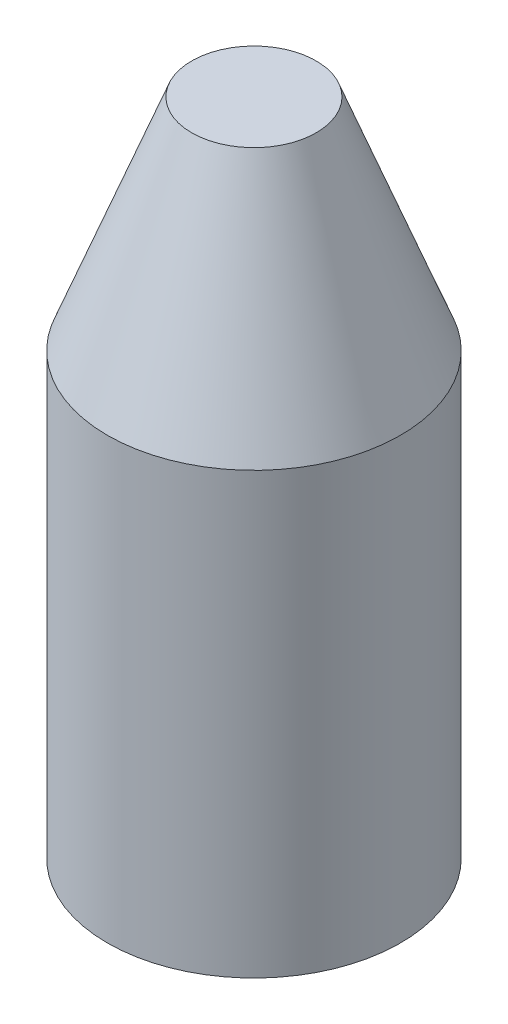
SolidWorks part; units mm, degrees
ref_plane "Front Plane" through (0, 0, 0) normal (0, 0, 1) x (1, 0, 0)
ref_plane "Top Plane" through (0, 0, 0) normal (0, 1, 0) x (1, 0, 0)
ref_plane "Right Plane" through (0, 0, 0) normal (1, 0, 0) x (0, 0, -1)
sketch "Sketch1" plane through (0, 0, 0) normal (0, 0, 1) x (1, 0, 0)
  line L0 (0, 22.5) -> (0, -22.5) construction
  line L1 (0, 22.5) -> (4.2489, 22.5)
  line L2 (4.2489, 22.5) -> (10, 7.5)
  line L3 (10, 7.5) -> (10, -22.5)
  line L4 (10, -22.5) -> (0, -22.5)
  line L5 (0, 22.5) -> (0, -22.5)
  point P2 (4.2489, 22.5)
  point P4 (0, 0)
  point P7 (0, 0)
  dimension "D1" = 30
  dimension "D2" = 15
  dimension "D3" = 20
revolve "Revolve1" add sketch "Sketch1" angle 360 about L0
